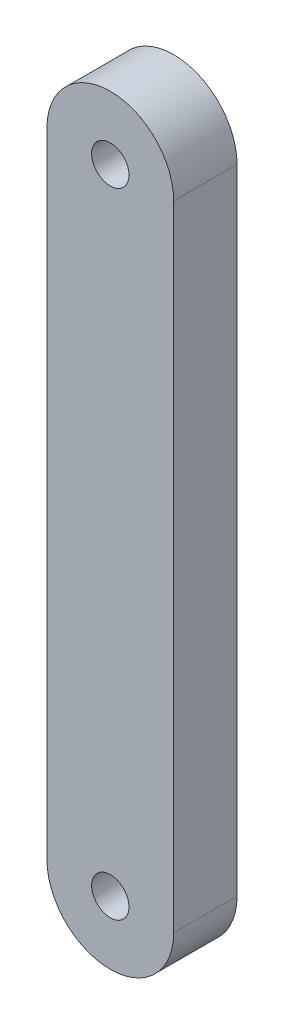
SolidWorks part; units mm, degrees
ref_plane "Front Plane" through (0, 0, 0) normal (0, 0, 1) x (1, 0, 0)
ref_plane "Top Plane" through (0, 0, 0) normal (0, 1, 0) x (1, 0, 0)
ref_plane "Right Plane" through (0, 0, 0) normal (1, 0, 0) x (0, 0, -1)
sketch "Sketch1" plane through (0, 0, 0) normal (0, 0, 1) x (1, 0, 0)
  line L0 (0, 25) -> (0, -25) construction
  line L1 (5, 25) -> (5, -25)
  line L2 (-5, 25) -> (-5, -25)
  arc A0 (5, 25) -> (-5, 25) centre (0, 25) ccw
  arc A1 (-5, -25) -> (5, -25) centre (0, -25) ccw
  point P3 (0, 0)
  dimension "D1" = 10
  dimension "D2" = 50
extrude "Boss-Extrude1" add sketch "Sketch1" along normal blind 5
sketch "Sketch2" plane through (0, 0, 0) normal (0, 0, -1) x (-1, 0, 0)
  circle A0 centre (0, -25) radius 1.475
  circle A1 centre (0, 25) radius 1.475
  point P6 (0, 0)
  dimension "D1" = 2.95
extrude "Cut-Extrude1" cut sketch "Sketch2" against normal blind 10
